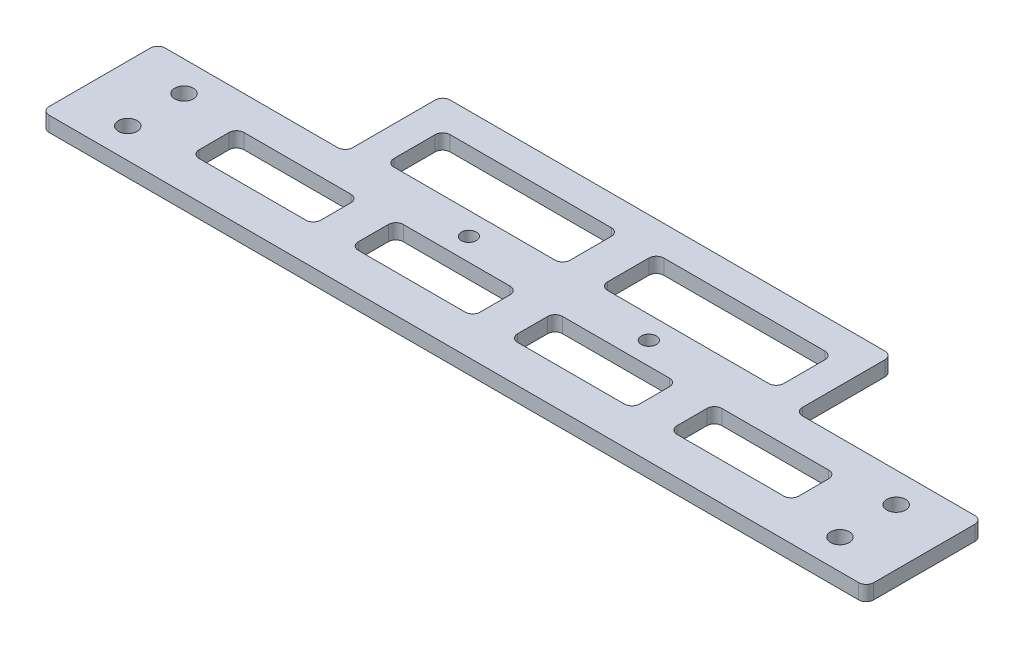
SolidWorks part; units mm, degrees
material "Thornel Mat VMA"
ref_plane "前视基准面" through (0, 0, 0) normal (0, 0, 1) x (1, 0, 0)
ref_plane "上视基准面" through (0, 0, 0) normal (0, 1, 0) x (1, 0, 0)
ref_plane "右视基准面" through (0, 0, 0) normal (1, 0, 0) x (0, 0, -1)
sketch "草图1" plane through (0, 0, 0) normal (0, 1, 0) x (1, 0, 0)
  line L0 (-47.5, 3.75) -> (47.5, -3.75) construction
  line L1 (-47.5, 3.75) -> (47.5, 3.75) construction
  line L2 (-47.5, 3.75) -> (-47.5, -3.75) construction
  line L3 (-47.5, -3.75) -> (47.5, -3.75) construction
  line L4 (47.5, 3.75) -> (47.5, -3.75) construction
  line L5 (30, 7.75) -> (55, 7.75)
  line L6 (-55, 7.75) -> (-30, 7.75)
  line L7 (-55, 7.75) -> (-55, -7.75)
  line L8 (-55, -7.75) -> (55, -7.75)
  line L9 (55, 7.75) -> (55, -7.75)
  line L11 (-30, 7.75) -> (-30, 20.75)
  line L12 (-30, 20.75) -> (30, 20.75)
  line L13 (30, 7.75) -> (30, 20.75)
  line L14 (-12, 6.25) -> (12, 6.25) construction
  line L15 (0, 0) -> (0, 6.25) construction
  circle A0 centre (-47.5, 3.75) radius 1.25
  circle A1 centre (-47.5, -3.75) radius 1.25
  circle A2 centre (47.5, 3.75) radius 1.25
  circle A3 centre (47.5, -3.75) radius 1.25
  circle A4 centre (-12, 6.25) radius 1
  circle A5 centre (12, 6.25) radius 1
  dimension "D5" = 2.5
  dimension "D11" = 2
  dimension "D1" = 7.5
  dimension "D2" = 95
  dimension "D3" = 7.5
  dimension "D4" = 4
  dimension "D6" = 7.5
  dimension "D7" = 60
  dimension "D8" = 4
  dimension "D9" = 13
  dimension "D10" = 24
  dimension "D12" = 14.5
extrude "凸台-拉伸1" add sketch "草图1" along normal blind 2
sketch "草图2" plane through (0, 2, 0) normal (0, 1, 0) x (1, 0, 0)
  line L0 (-55, 7.75) -> (-55, -7.75) construction
  line L1 (-40, 3.25) -> (-23.75, 3.25)
  line L2 (-40, 3.25) -> (-40, -2.75)
  line L3 (-40, -2.75) -> (-23.75, -2.75)
  line L4 (-23.75, 3.25) -> (-23.75, -2.75)
  line L5 (-18.75, 3.25) -> (-2.5, 3.25)
  line L6 (-18.75, 3.25) -> (-18.75, -2.75)
  line L7 (-18.75, -2.75) -> (-2.5, -2.75)
  line L8 (-2.5, 3.25) -> (-2.5, -2.75)
  line L10 (-55, -7.75) -> (55, -7.75) construction
  line L11 (-23.75, -2.75) -> (-18.75, -2.75) construction
  line L12 (-2.5, -2.75) -> (2.5, -2.75) construction
  line L13 (0, -1.1) -> (0, 1.1) construction
  line L14 (-30, 20.75) -> (-30, 7.75) construction
  line L15 (2.5, 3.25) -> (2.5, -2.75)
  line L16 (18.75, -2.75) -> (2.5, -2.75)
  line L17 (18.75, 3.25) -> (18.75, -2.75)
  line L18 (18.75, 3.25) -> (2.5, 3.25)
  line L19 (23.75, 3.25) -> (23.75, -2.75)
  line L20 (40, -2.75) -> (23.75, -2.75)
  line L21 (40, 3.25) -> (40, -2.75)
  line L22 (40, 3.25) -> (23.75, 3.25)
  line L23 (-26, 16.75) -> (-2.5, 16.75)
  line L24 (-26, 16.75) -> (-26, 9.25)
  line L25 (-26, 9.25) -> (-2.5, 9.25)
  line L26 (-2.5, 16.75) -> (-2.5, 9.25)
  line L27 (30, 20.75) -> (-30, 20.75) construction
  line L28 (2.5, 16.75) -> (2.5, 9.25)
  line L29 (26, 9.25) -> (2.5, 9.25)
  line L30 (26, 16.75) -> (26, 9.25)
  line L31 (26, 16.75) -> (2.5, 16.75)
  circle A0 centre (-12, 6.25) radius 1 construction
  dimension "D7" = 3
  dimension "D2" = 3
  dimension "D1" = 15
  dimension "D3" = 5
  dimension "D4" = 5
  dimension "D5" = 4
  dimension "D6" = 4
extrude "切除-拉伸1" cut sketch "草图2" against normal through all
fillet "圆角1" radius 1 32 edges at (-55, 1, 7.75) (55, 1, 7.75) (-55, 1, -7.75) (-2.5, 1, -3.25) (-2.5, 1, 2.75) (-18.75, 1, 2.75) (-18.75, 1, -3.25) (23.75, 1, -3.25) (40, 1, -3.25) (40, 1, 2.75) (23.75, 1, 2.75) (2.5, 1, 2.75) (2.5, 1, -3.25) (18.75, 1, -3.25) (18.75, 1, 2.75) (-23.75, 1, 2.75) (-40, 1, 2.75) (-23.75, 1, -3.25) (-40, 1, -3.25) (-30, 1, -7.75) (30, 1, -20.75) (30, 1, -7.75) (55, 1, -7.75) (-30, 1, -20.75) (26, 1, -9.25) (2.5, 1, -9.25) (2.5, 1, -16.75) (26, 1, -16.75) (-2.5, 1, -16.75) (-2.5, 1, -9.25) (-26, 1, -16.75) (-26, 1, -9.25)
